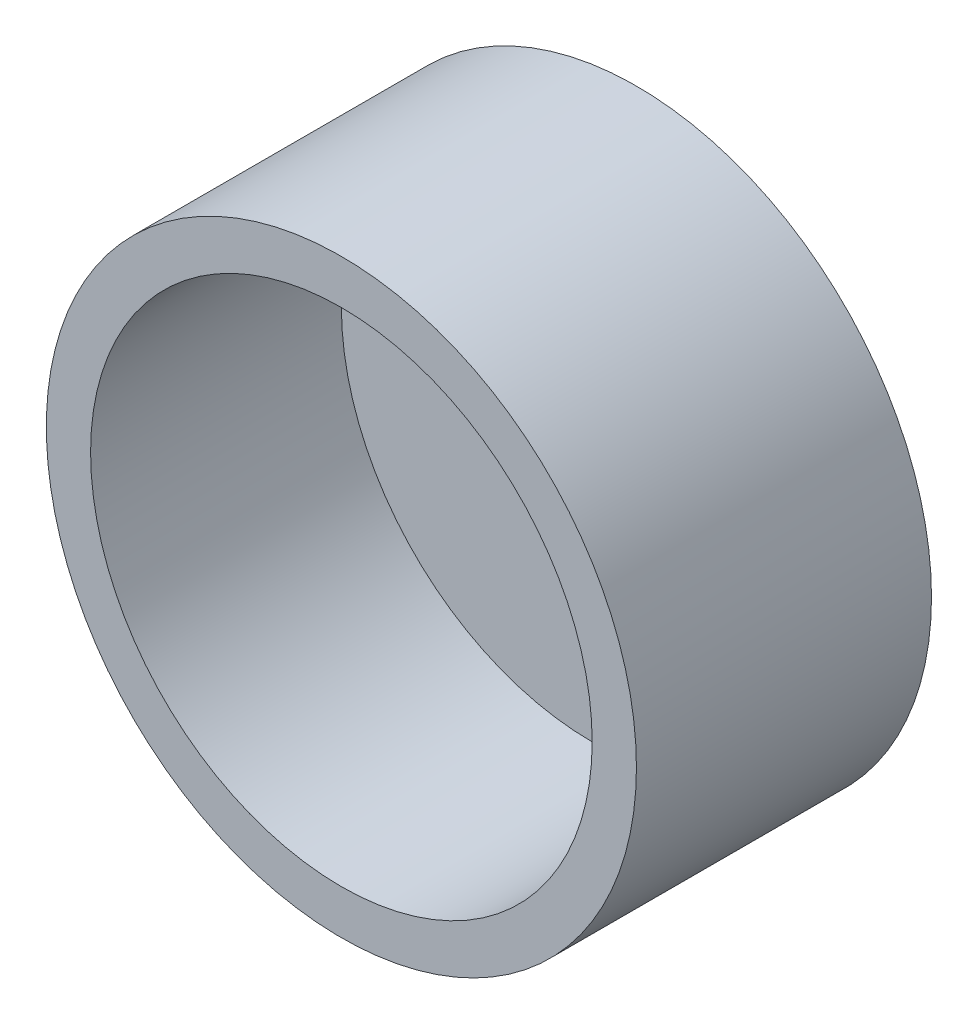
SolidWorks part; units mm, degrees
ref_plane "前视基准面" through (0, 0, 0) normal (0, 0, 1) x (1, 0, 0)
ref_plane "上视基准面" through (0, 0, 0) normal (0, 1, 0) x (1, 0, 0)
ref_plane "右视基准面" through (0, 0, 0) normal (1, 0, 0) x (0, 0, -1)
ref_plane "基准面1" through (0, 40, 0) normal (0, 1, 0) x (1, 0, 0)
sketch "草图3" plane through (0, 0, 0) normal (0, 0, 1) x (1, 0, 0)
  circle A0 centre (0, 0) radius 40
extrude "凸台-拉伸2" add sketch "草图3" along normal blind 40
ref_plane "基准面2" through (0, 0, 40) normal (0, 0, 1) x (1, 0, 0)
sketch "草图4" plane through (0, 0, 40) normal (0, 0, 1) x (1, 0, 0)
  circle A0 centre (0, 0) radius 34
extrude "切除-拉伸2" cut sketch "草图4" against normal blind 34
